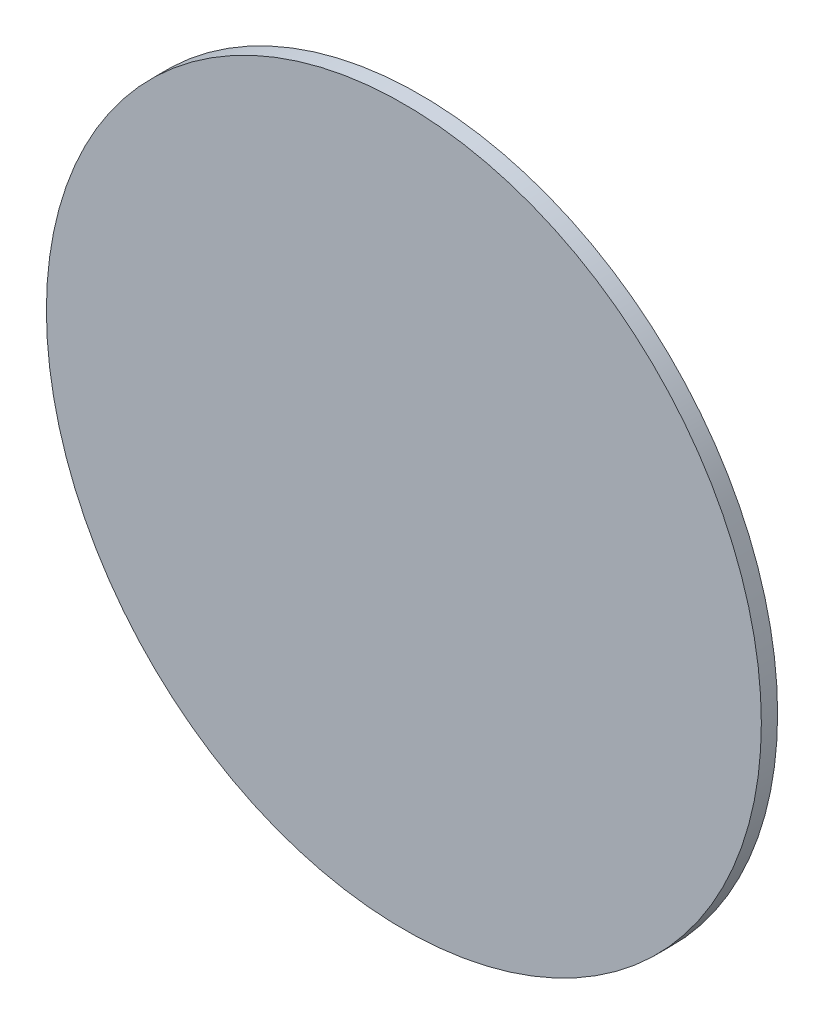
SolidWorks part; units mm, degrees
material "2A12"
ref_plane "前视基准面" through (0, 0, 0) normal (0, 0, 1) x (1, 0, 0)
ref_plane "上视基准面" through (0, 0, 0) normal (0, 1, 0) x (1, 0, 0)
ref_plane "右视基准面" through (0, 0, 0) normal (1, 0, 0) x (0, 0, -1)
sketch "草图1" plane through (0, 0, 0) normal (0, 0, 1) x (1, 0, 0)
  circle A0 centre (0, 0) radius 110
  dimension "D1" = 220
extrude "凸台-拉伸1" add sketch "草图1" along normal blind 5
